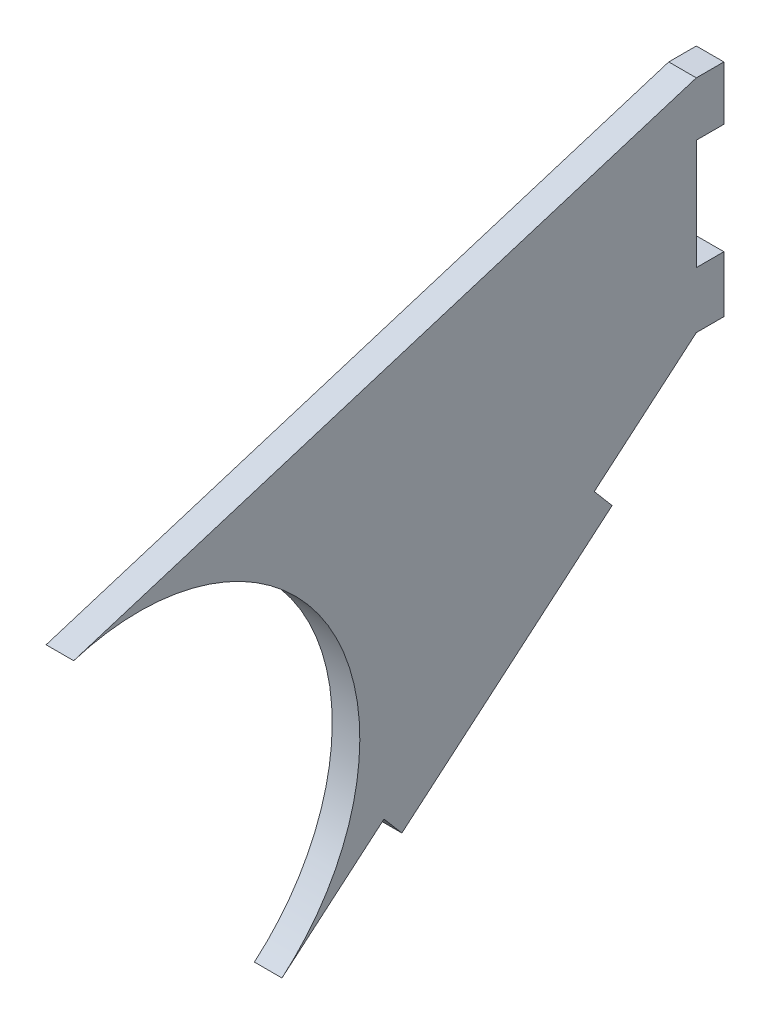
SolidWorks part; units mm, degrees
material "AISI 4130 Steel, annealed at 865C"
ref_plane "X-Y Datum" through (0, 0, 0) normal (0, 0, 1) x (1, 0, 0)
ref_plane "X-Z Datum" through (0, 0, 0) normal (0, 1, 0) x (1, 0, 0)
ref_plane "Y-Z Datum" through (0, 0, 0) normal (1, 0, 0) x (0, 0, -1)
sketch "Sketch1" plane through (0, 0, 0) normal (1, 0, 0) x (0, 0, -1)
  line L1 (-6.2138, -6.4158) -> (-0.4008, -6.4158) construction
  line L2 (0, -6.4158) -> (-23.8483, -26.6616)
  line L3 (0, 6.2842) -> (-35.8363, -4.852)
  line L4 (0, 55) -> (0, -55) construction
  line L5 (0, -6.4158) -> (0, 6.2842)
  line L6 (0, -6.4158) -> (1.5875, -6.4158)
  line L7 (1.5875, -6.4158) -> (1.5875, -3.175)
  line L8 (1.5875, -3.175) -> (0, -3.175)
  line L9 (0, 6.2842) -> (1.5875, 6.2842)
  line L10 (1.5875, 6.2842) -> (1.5875, 3.175)
  line L11 (1.5875, 3.175) -> (0, 3.175)
  line L12 (1.5875, -3.175) -> (1.5875, 3.175) construction
  line L13 (-16.9478, -22.8859) -> (-4.8457, -12.6119)
  line L14 (-10.8968, -17.7489) -> (-11.9242, -16.5387) construction
  line L15 (-16.9478, -22.8859) -> (-17.9752, -21.6757)
  line L16 (-5.8731, -11.4017) -> (-4.8457, -12.6119)
  arc A0 (-23.8483, -26.6616) -> (-35.8363, -4.852) centre (-32.0675, -16.9799) ccw
  point P4 (1.5875, 0)
  point P5 (-11.0505, -17.8351)
  point P21 (-10.0168, -18.7855)
  dimension "D1" = 25.4
  dimension "D2" = 12.7
  dimension "D3" = 1.5875
  dimension "D4" = 6.35
  dimension "D5" = 15.875
extrude "Boss-Extrude1" add sketch "Sketch1" along normal blind 1.5875
